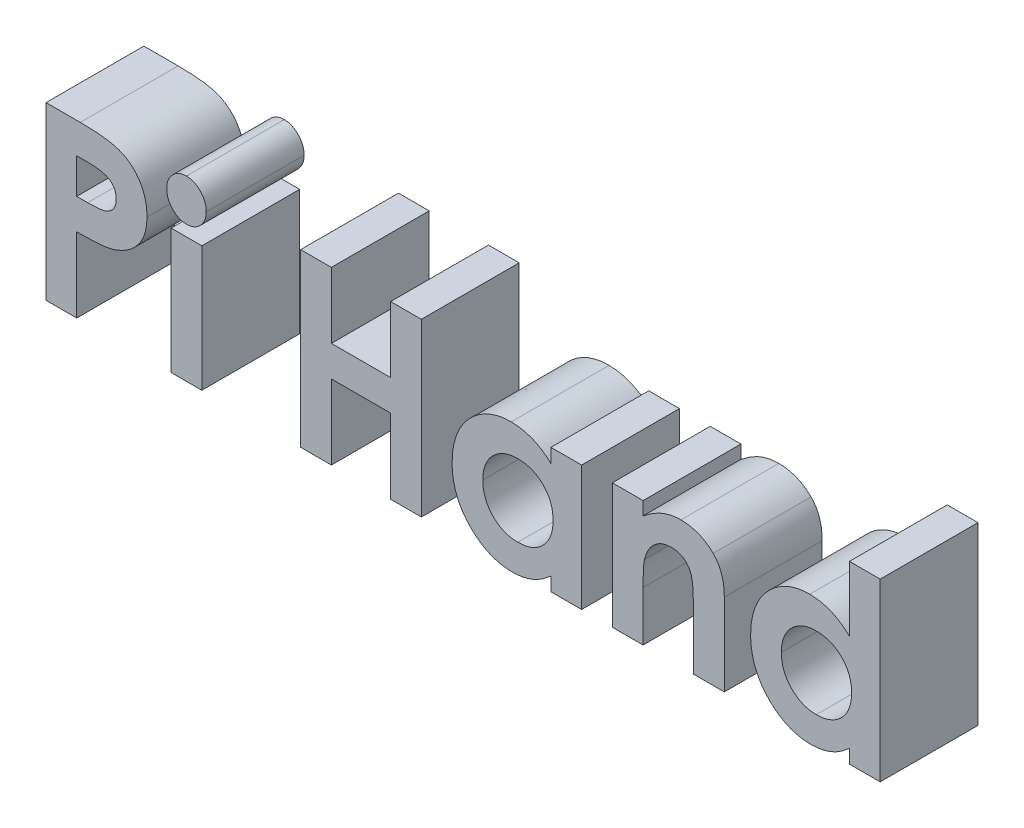
SolidWorks part; units mm, degrees
ref_plane "Front Plane" through (0, 0, 0) normal (0, 0, 1) x (1, 0, 0)
ref_plane "Top Plane" through (0, 0, 0) normal (0, 1, 0) x (1, 0, 0)
ref_plane "Right Plane" through (0, 0, 0) normal (1, 0, 0) x (0, 0, -1)
sketch "Sketch1" plane through (0, 0, 0) normal (0, 0, 1) x (1, 0, 0)
  text T0 "<b>Pi Hand</b>"
extrude "Boss-Extrude1" add sketch "Sketch1" along normal blind 2
